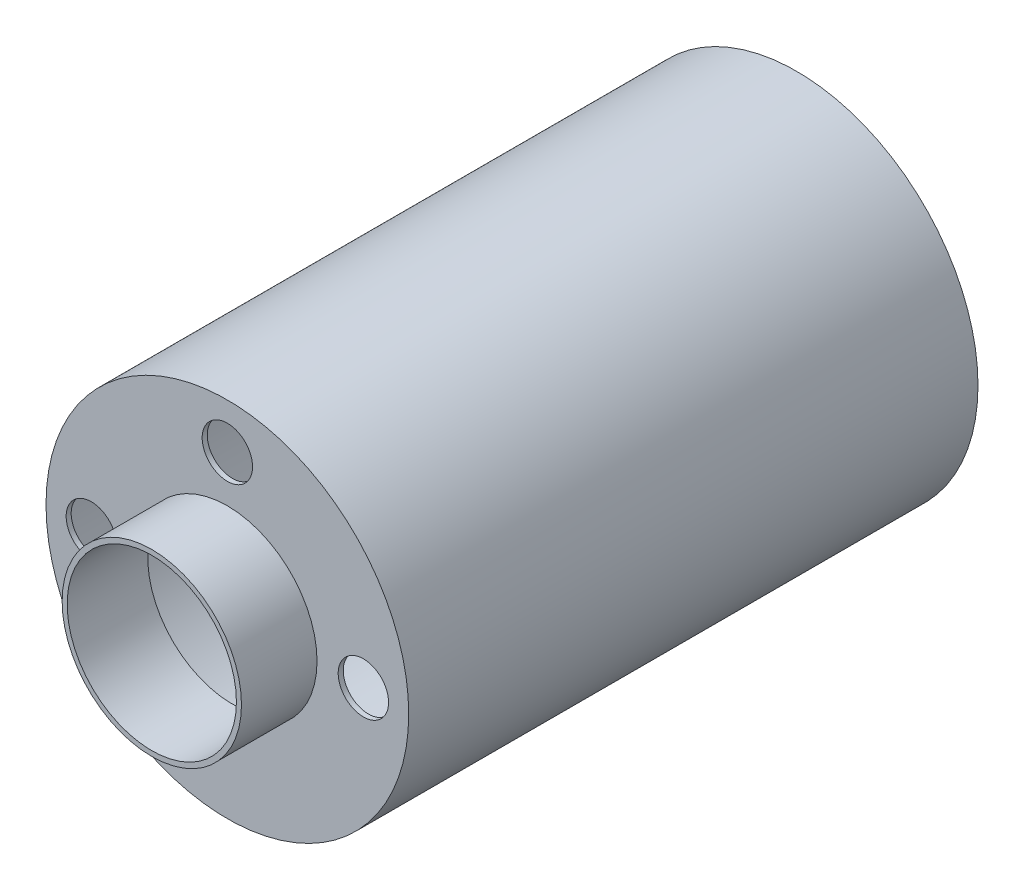
SolidWorks part; units mm, degrees
ref_plane "Front Plane" through (0, 0, 0) normal (0, 0, 1) x (1, 0, 0)
ref_plane "Top Plane" through (0, 0, 0) normal (0, 1, 0) x (1, 0, 0)
ref_plane "Right Plane" through (0, 0, 0) normal (1, 0, 0) x (0, 0, -1)
sketch "Sketch1" plane through (0, 0, 0) normal (0, 0, 1) x (1, 0, 0)
  circle A0 centre (0, 0) radius 18
  dimension "D1" = 36
extrude "Boss-Extrude1" add sketch "Sketch1" along normal mid plane 56.5
sketch "Sketch2" plane through (0, 0, 28.25) normal (0, 0, 1) x (1, 0, 0)
  circle A0 centre (0, 0) radius 8.9
  dimension "D1" = 17.8
extrude "Boss-Extrude2" add sketch "Sketch2" along normal blind 7.5
shell "Shell1" thickness 0.5
sketch "Sketch4" plane through (0, 0, 28.25) normal (0, 0, 1) x (1, 0, 0)
  circle A0 centre (-13.5, 0) radius 2.5
  circle A1 centre (0, 13.5) radius 2.5
  circle A2 centre (13.5, 0) radius 2.5
  point P10 (0, 0)
  dimension "D1" = 5
  dimension "D2" = 13.5
  dimension "D3" = 3
extrude "Cut-Extrude1" cut sketch "Sketch4" against normal blind 7.5
